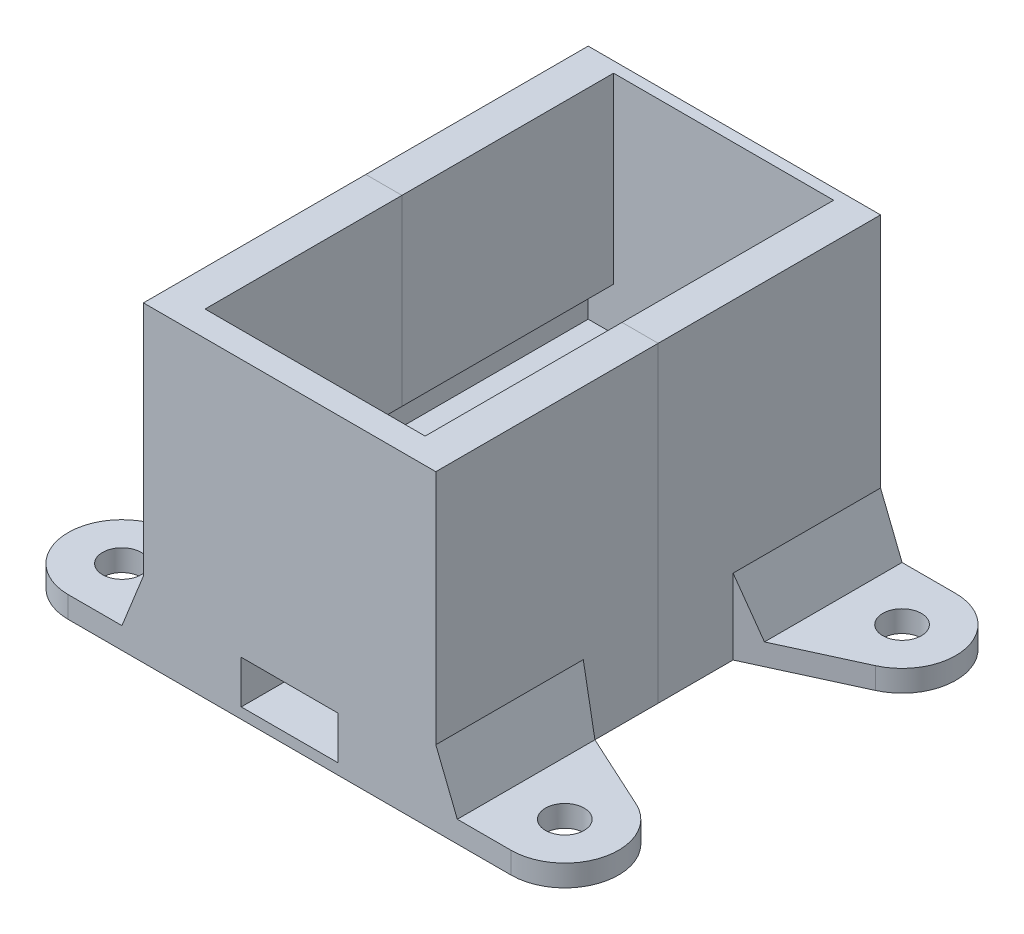
SolidWorks part; units mm, degrees
ref_plane "Front Plane" through (0, 0, 0) normal (0, 0, 1) x (1, 0, 0)
ref_plane "Top Plane" through (0, 0, 0) normal (0, 1, 0) x (1, 0, 0)
ref_plane "Right Plane" through (0, 0, 0) normal (1, 0, 0) x (0, 0, -1)
sketch "Sketch3" plane through (0, 0, 0) normal (0, 1, 0) x (1, 0, 0)
  line L0 (0, 26.035) -> (0, -26.505) construction
  line L1 (-11.2395, -19.05) -> (11.2395, -19.05)
  line L2 (-11.2395, -19.05) -> (-11.2395, 19.05)
  line L3 (-11.2395, 19.05) -> (11.2395, 19.05)
  line L4 (11.2395, -19.05) -> (11.2395, 19.05)
  line L5 (-11.2395, -19.05) -> (11.2395, 19.05) construction
  line L6 (-11.2395, 19.05) -> (11.2395, -19.05) construction
  line L7 (-17.27, 26.035) -> (17.27, 26.035)
  line L8 (-17.27, 26.035) -> (-17.27, -26.505)
  line L9 (-17.27, -26.505) -> (17.27, -26.505)
  line L10 (17.27, 26.035) -> (17.27, -26.505)
  line L11 (0, 19.05) -> (0, -19.05) construction
  point P0 (0, 0)
  dimension "D1" = 22.479
  dimension "D2" = 38.1
  dimension "D3" = 34.54
  dimension "D4" = 6.985
  dimension "D5" = 52.54
extrude "Boss-Extrude1" add sketch "Sketch3" along normal blind 10.16
sketch "Sketch4" plane through (0, 10.16, 0) normal (0, 1, 0) x (1, 0, 0)
  line L1 (-17.27, -26.505) -> (17.27, -26.505)
  line L2 (-17.27, -26.505) -> (-17.27, 26.035)
  line L3 (-17.27, 26.035) -> (17.27, 26.035)
  line L4 (17.27, -26.505) -> (17.27, 26.035)
  line L5 (-16, 24.765) -> (16, 24.765)
  line L6 (-16, 24.765) -> (-16, -25.235)
  line L7 (-16, -25.235) -> (16, -25.235)
  line L8 (16, 24.765) -> (16, -25.235)
  dimension "D1" = 1.27
  dimension "D2" = 1.27
  dimension "D3" = 50
  dimension "D4" = 32
extrude "Boss-Extrude2" add sketch "Sketch4" along normal blind 5.08
sketch "Sketch6" plane through (0, 15.24, 0) normal (0, 1, 0) x (1, 0, 0)
  line L0 (16, 24.765) -> (-16, 24.765) construction
  line L1 (-17.27, 26.035) -> (17.27, 26.035)
  line L2 (-17.27, 26.035) -> (-17.27, -26.505)
  line L3 (-17.27, -26.505) -> (17.27, -26.505)
  line L4 (17.27, 26.035) -> (17.27, -26.505)
  line L5 (-13, 24.765) -> (13, 24.765)
  line L6 (-13, 24.765) -> (-13, -23.495)
  line L7 (-13, -23.495) -> (13, -23.495)
  line L8 (13, 24.765) -> (13, -23.495)
  line L11 (0, 26.035) -> (0, -26.505) construction
  line L12 (0, -26.505) -> (0, -23.495) construction
  line L13 (0, -23.495) -> (0, 24.765) construction
  dimension "D1" = 26
  dimension "D2" = 48.26
extrude "Boss-Extrude3" add sketch "Sketch6" along normal blind 21.59
sketch "Sketch8" plane through (0, 0, 26.505) normal (0, 0, 1) x (1, 0, 0)
  line L0 (0, 6.35) -> (0, 1.27) construction
  line L1 (-5.715, 1.27) -> (5.715, 1.27)
  line L2 (-5.715, 1.27) -> (-5.715, 6.35)
  line L3 (-5.715, 6.35) -> (5.715, 6.35)
  line L4 (5.715, 1.27) -> (5.715, 6.35)
  line L5 (0, 0) -> (0, 36.83) construction
  line L6 (-17.27, 0) -> (17.27, 0) construction
  line L7 (-17.27, 36.83) -> (17.27, 36.83) construction
  dimension "D1" = 1.27
  dimension "D2" = 11.43
  dimension "D3" = 5.08
extrude "Cut-Extrude1" cut sketch "Sketch8" against normal up to surface (52.54 mm away) up to face at (0, 18.415, -26.035)
sketch "Sketch9" plane through (0, 0, 0) normal (0, 0, 1) x (1, 0, 0)
  line L0 (17.27, 18.415) -> (30.1643, 0)
  line L1 (17.27, 36.83) -> (17.27, 0) construction
  line L2 (30.1643, 0) -> (17.27, 0)
  line L3 (17.27, 0) -> (17.27, 18.415)
  line L4 (0, 36.83) -> (0, 0) construction
  line L5 (-17.27, 36.83) -> (17.27, 36.83) construction
  line L6 (-30.1643, 0) -> (-17.27, 0)
  line L7 (-17.27, 0) -> (-17.27, 18.415)
  line L8 (-17.27, 18.415) -> (-30.1643, 0)
  dimension "D1" = 35
extrude "Boss-Extrude4" [suppressed] add sketch "Sketch9" along normal up to surface and the other way up to surface
sketch "Sketch12" plane through (0, 0, 0) normal (0, 1, 0) x (1, 0, 0)
  line L0 (17.27, -26.505) -> (17.27, 26.035) construction
  line L1 (17.27, 26.035) -> (-17.27, 26.035) construction
  line L2 (26.16, 26.035) -> (17.27, 26.035)
  line L3 (17.27, 26.035) -> (17.27, 8.6134)
  line L4 (28.8106, 13.9147) -> (17.27, 8.6134)
  line L5 (0, 26.035) -> (0, -26.505) construction
  line L6 (-17.27, -26.505) -> (17.27, -26.505) construction
  line L7 (-17.27, -0.235) -> (17.27, -0.235) construction
  line L8 (-17.27, 26.035) -> (-17.27, -26.505) construction
  line L9 (26.16, -26.505) -> (17.27, -26.505)
  line L10 (17.27, -26.505) -> (17.27, -9.0834)
  line L11 (28.8106, -14.3847) -> (17.27, -9.0834)
  line L12 (-28.8106, -14.3847) -> (-17.27, -9.0834)
  line L13 (-17.27, -26.505) -> (-17.27, -9.0834)
  line L14 (-26.16, -26.505) -> (-17.27, -26.505)
  line L15 (-28.8106, 13.9147) -> (-17.27, 8.6134)
  line L16 (-17.27, 26.035) -> (-17.27, 8.6134)
  line L17 (-26.16, 26.035) -> (-17.27, 26.035)
  circle A0 centre (26.16, 19.685) radius 6.35
  circle A1 centre (26.16, -20.155) radius 6.35
  circle A2 centre (-26.16, -20.155) radius 6.35
  circle A3 centre (-26.16, 19.685) radius 6.35
  dimension "D1" = 12.7
  dimension "D3" = 8.89
  dimension "D2" = 12.7
  dimension "D4" = 17.4216
extrude "Boss-Extrude5" add sketch "Sketch12" along normal blind 2.54 contours A2 L13 L12 | A2 | A2 L14 L13 | L16 A3 L15 | L17 A3 L16 | A3 | A1 | L10 A1 L11 | L9 A1 L10 | A0 L3 L4 | A0 | A0 L2 L3
sketch "Sketch13" plane through (0, 2.54, 0) normal (0, 1, 0) x (1, 0, 0)
  line L0 (0, 26.035) -> (0, -26.505) construction
  line L1 (26.16, 26.035) -> (-26.16, 26.035) construction
  line L2 (-17.27, -0.235) -> (17.27, -0.235) construction
  circle A0 centre (26.16, 19.685) radius 2.286
  circle A1 centre (26.16, 19.685) radius 6.35 construction
  circle A2 centre (26.16, -20.155) radius 2.286
  circle A3 centre (-26.16, -20.155) radius 2.286
  circle A4 centre (-26.16, 19.685) radius 2.286
  dimension "D1" = 4.572
extrude "Cut-Extrude6" cut sketch "Sketch13" against normal up to surface (2.54 mm away) up to face at (0, 0, 0.235)
sketch "Sketch14" plane through (0, 0, 26.505) normal (0, 0, 1) x (1, 0, 0)
  line L0 (17.27, 8.89) -> (19.81, 2.54)
  line L1 (17.27, 36.83) -> (17.27, 2.54) construction
  line L2 (26.16, 2.54) -> (17.27, 2.54) construction
  line L3 (19.81, 2.54) -> (17.27, 2.54)
  line L4 (17.27, 2.54) -> (17.27, 8.89)
  dimension "D1" = 2.54
  dimension "D2" = 6.35
extrude "Boss-Extrude6" add sketch "Sketch14" against normal blind 17.4216
sketch "Sketch15" plane through (0, 2.54, 0) normal (0, -1, 0) x (1, 0, 0)
  line L0 (17.27, 9.0834) -> (19.81, 10.2502)
  line L1 (19.81, 10.2502) -> (19.81, 9.0834)
  line L2 (19.81, 9.0834) -> (17.27, 9.0834)
extrude "Cut-Extrude7" cut sketch "Sketch15" against normal through all
mirror "Mirror4" about plane through (0, 0, 0) normal (1, 0, 0) of "Cut-Extrude7", "Boss-Extrude6"
ref_plane "Plane2" through (0, 0, 0.235) normal (0, 0, 1) x (1, 0, 0)
mirror "Mirror5" about plane through (0, 0, 0.235) normal (0, 0, 1) of "Mirror4", "Boss-Extrude6", "Cut-Extrude7"
ref_plane "Plane3" through (0, 0, 19.05) normal (0, 0, 1) x (1, 0, 0)
split "Split3" trim tools "Plane2" bodies to split 118 resulting bodies 122 123
